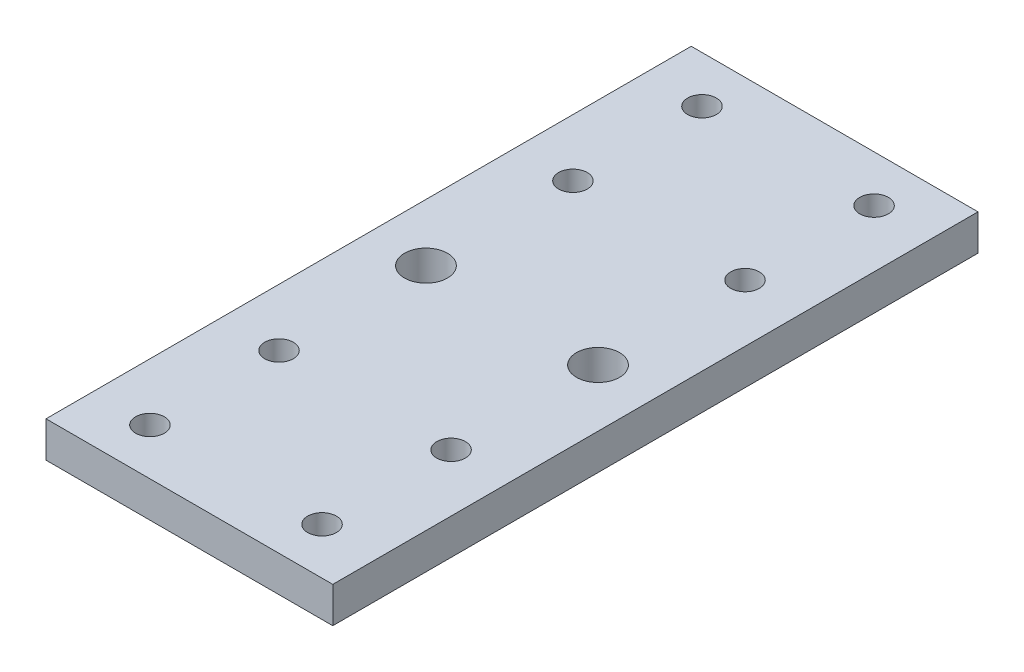
SolidWorks part; units mm, degrees
ref_plane "Front Plane" through (0, 0, 0) normal (0, 0, 1) x (1, 0, 0)
ref_plane "Top Plane" through (0, 0, 0) normal (0, 1, 0) x (1, 0, 0)
ref_plane "Right Plane" through (0, 0, 0) normal (1, 0, 0) x (0, 0, -1)
sketch "Sketch1" plane through (0, 0, 0) normal (0, 1, 0) x (1, 0, 0)
  line L0 (20, 0) -> (-20, 0) construction
  line L1 (-20, -45) -> (20, -45)
  line L2 (-20, -45) -> (-20, 45)
  line L3 (-20, 45) -> (20, 45)
  line L4 (20, -45) -> (20, 45)
  line L5 (-20, -45) -> (20, 45) construction
  line L6 (-20, 45) -> (20, -45) construction
  line L7 (0, 0) -> (0, 10.0205) construction
  circle A0 centre (-12, -38.5) radius 2
  circle A1 centre (-12, -20.5) radius 2
  circle A2 centre (-12, 20.5) radius 2
  circle A3 centre (-12, 38.5) radius 2
  circle A4 centre (12, 38.5) radius 2
  circle A6 centre (12, -20.5) radius 2
  circle A7 centre (12, -38.5) radius 2
  circle A8 centre (12, 20.5) radius 2
  circle A9 centre (-12, 0) radius 3
  circle A10 centre (12, 0) radius 3
  point P0 (0, 0)
  dimension "D3" = 6
  dimension "D1" = 40
  dimension "D2" = 90
  dimension "D4" = 8
extrude "Boss-Extrude1" add sketch "Sketch1" along normal blind 5
